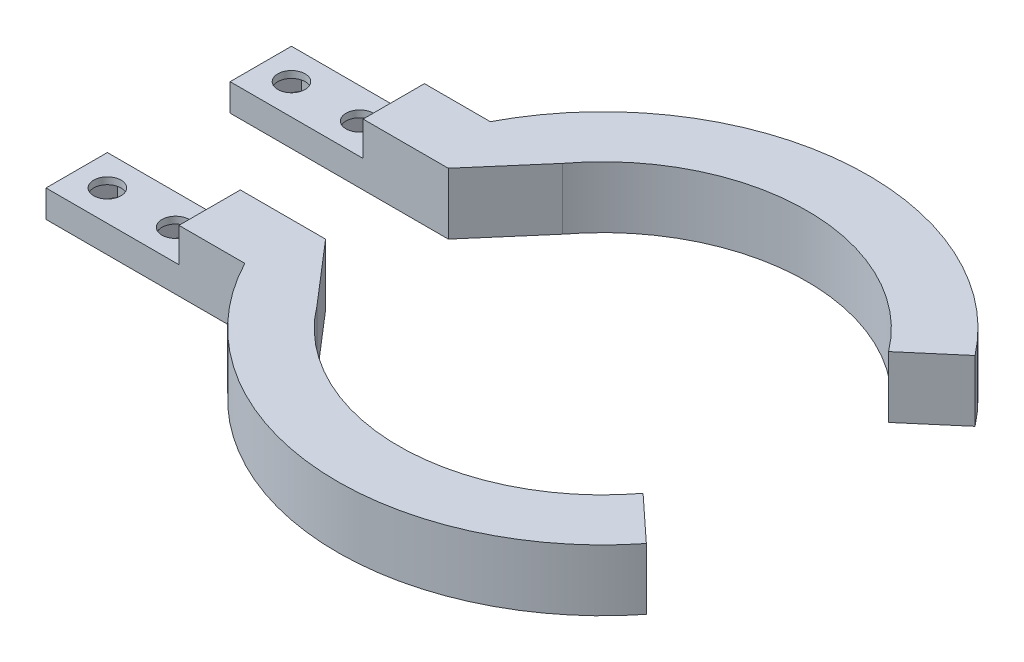
SolidWorks part; units mm, degrees
ref_plane "Front Plane" through (0, 0, 0) normal (0, 0, 1) x (1, 0, 0)
ref_plane "Top Plane" through (0, 0, 0) normal (0, 1, 0) x (1, 0, 0)
ref_plane "Right Plane" through (0, 0, 0) normal (1, 0, 0) x (0, 0, -1)
sketch "Sketch1" plane through (0, 0, 0) normal (0, 1, 0) x (1, 0, 0)
  line L0 (23.9061, 18) -> (30.748, 23.8472)
  line L1 (-34.4982, 18) -> (-23.9061, 18)
  line L3 (-34.4982, -18) -> (-23.9061, -18)
  line L5 (23.9061, -18) -> (30.5213, -24.1366)
  line L7 (-23.9061, 18) -> (-63.6593, 18)
  line L8 (-23.9061, 18) -> (-31.6593, 9)
  line L9 (-31.6593, 9) -> (-63.6593, 9)
  line L10 (-63.6593, 18) -> (-63.6593, 9)
  line L11 (-23.9061, -18) -> (-63.6593, -18)
  line L12 (-23.9061, -18) -> (-31.6593, -9)
  line L13 (-31.6593, -9) -> (-63.6593, -9)
  line L14 (-63.6593, -18) -> (-63.6593, -9)
  arc A0 (-23.9061, -18) -> (23.9061, -18) centre (0, 0) ccw
  arc A1 (-34.4982, -18) -> (30.5213, -24.1366) centre (0, 0) ccw
  arc A2 (23.9061, 18) -> (-23.9061, 18) centre (0, 0) ccw
  arc A3 (30.748, 23.8472) -> (-34.4982, 18) centre (0, 0) ccw
  circle A4 centre (-59.1593, 13.5) radius 2
  circle A5 centre (-49.1593, 13.5) radius 2
  circle A6 centre (-59.1593, -13.5) radius 2
  circle A7 centre (-49.1593, -13.5) radius 2
  point P24 (30.7321, 23.8337)
  point P25 (0, 0)
  point P26 (34.5449, -19.5534)
  point P27 (31.4159, -24.681)
  dimension "D1" = 9
  dimension "D7" = 4.5
  dimension "D8" = 4.5
  dimension "D9" = 10
  dimension "D10" = 0
  dimension "D11" = 4.5
  dimension "D12" = 4.5
  dimension "D13" = 0
  dimension "D14" = 10
  dimension "D2" = 18
  dimension "D3" = 9
  dimension "D4" = 32
  dimension "D5" = 32
  dimension "D6" = 18
  dimension "D15" = 9
extrude "Boss-Extrude1" add sketch "Sketch1" along normal blind 9 contours L7 L10 L9 L8 L1 A5 A4 | L14 L11 L3 L12 L13 A7 A6 | L0 A3 L1 A2 | L3 A1 L5 A0
sketch "Sketch5" plane through (0, 9, 0) normal (0, 1, 0) x (1, 0, 0)
  line L0 (-34.4982, -18) -> (-63.6593, -18) construction
  line L1 (-63.6593, 18) -> (-44.1593, 18)
  line L2 (-63.6593, 18) -> (-63.6593, -18)
  line L3 (-63.6593, -18) -> (-44.1593, -18)
  line L4 (-44.1593, 18) -> (-44.1593, -18)
  circle A0 centre (-49.1593, 13.5) radius 2 construction
  dimension "D1" = 5
extrude "Cut-Extrude1" cut sketch "Sketch5" against normal blind 5
sketch "Sketch6" plane through (0, 0, 0) normal (0, -1, 0) x (1, 0, 0)
  line L1 (-57.1097, 9.95) -> (-55.0601, 13.5)
  line L2 (-55.0601, 13.5) -> (-57.1097, 17.05)
  line L3 (-57.1097, 17.05) -> (-61.2089, 17.05)
  line L4 (-61.2089, 17.05) -> (-63.2585, 13.5)
  line L5 (-63.2585, 13.5) -> (-61.2089, 9.95)
  line L6 (-61.2089, 9.95) -> (-57.1097, 9.95)
  line L7 (-47.1097, 9.95) -> (-45.0601, 13.5)
  line L8 (-45.0601, 13.5) -> (-47.1097, 17.05)
  line L9 (-47.1097, 17.05) -> (-51.2089, 17.05)
  line L10 (-51.2089, 17.05) -> (-53.2585, 13.5)
  line L11 (-53.2585, 13.5) -> (-51.2089, 9.95)
  line L12 (-51.2089, 9.95) -> (-47.1097, 9.95)
  line L13 (-61.2089, -17.05) -> (-57.1097, -17.05)
  line L14 (-57.1097, -17.05) -> (-55.0601, -13.5)
  line L15 (-55.0601, -13.5) -> (-57.1097, -9.95)
  line L16 (-57.1097, -9.95) -> (-61.2089, -9.95)
  line L17 (-61.2089, -9.95) -> (-63.2585, -13.5)
  line L18 (-63.2585, -13.5) -> (-61.2089, -17.05)
  line L19 (-47.1097, -17.05) -> (-45.0601, -13.5)
  line L20 (-45.0601, -13.5) -> (-47.1097, -9.95)
  line L21 (-47.1097, -9.95) -> (-51.2089, -9.95)
  line L22 (-51.2089, -9.95) -> (-53.2585, -13.5)
  line L23 (-53.2585, -13.5) -> (-51.2089, -17.05)
  line L24 (-51.2089, -17.05) -> (-47.1097, -17.05)
  circle A0 centre (-59.1593, 13.5) radius 3.55 construction
  circle A1 centre (-49.1593, 13.5) radius 3.55 construction
  circle A2 centre (-59.1593, -13.5) radius 3.55 construction
  circle A3 centre (-49.1593, -13.5) radius 3.55 construction
extrude "Cut-Extrude2" cut sketch "Sketch6" against normal blind 3
